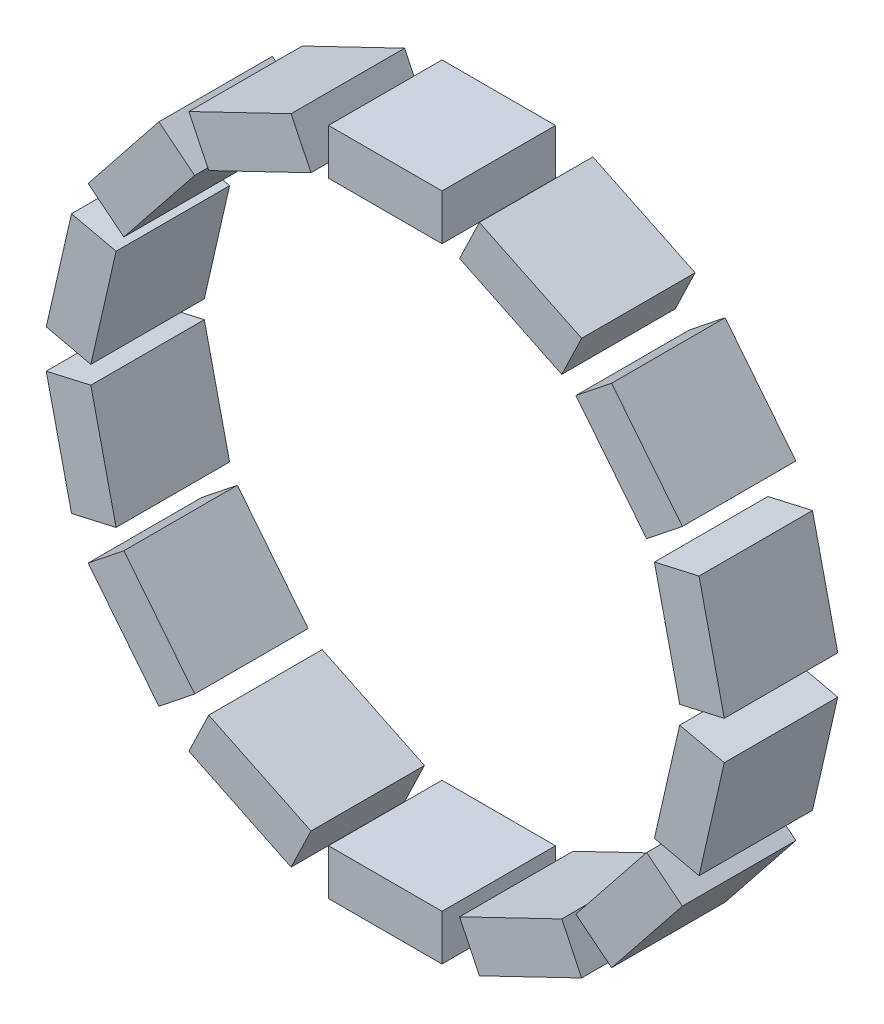
SolidWorks part; units mm, degrees
ref_plane "Front Plane" through (0, 0, 0) normal (0, 0, 1) x (1, 0, 0)
ref_plane "Top Plane" through (0, 0, 0) normal (0, 1, 0) x (1, 0, 0)
ref_plane "Right Plane" through (0, 0, 0) normal (1, 0, 0) x (0, 0, -1)
sketch "Sketch1" plane through (0, 0, 0) normal (0, 0, 1) x (1, 0, 0)
  line L0 (3.2594, 12.5053) -> (7.7448, 10.3452)
  line L1 (-2.4892, 14.6877) -> (2.4892, 14.6877)
  line L2 (-2.4892, 14.6877) -> (-2.4892, 12.6811)
  line L3 (-2.4892, 12.6811) -> (2.4892, 12.6811)
  line L4 (2.4892, 14.6877) -> (2.4892, 12.6811)
  line L5 (4.13, 14.3132) -> (3.2594, 12.5053)
  line L6 (4.13, 14.3132) -> (8.6154, 12.1531)
  line L7 (8.6154, 12.1531) -> (7.7448, 10.3452)
  line L8 (8.3625, 9.8526) -> (11.4664, 5.9604)
  line L9 (9.9313, 11.1037) -> (8.3625, 9.8526)
  line L10 (9.9313, 11.1037) -> (13.0353, 7.2115)
  line L11 (13.0353, 7.2115) -> (11.4664, 5.9604)
  line L12 (11.8092, 5.2486) -> (12.917, 0.395)
  line L13 (13.7655, 5.6951) -> (11.8092, 5.2486)
  line L14 (13.7655, 5.6951) -> (14.8733, 0.8415)
  line L15 (14.8733, 0.8415) -> (12.917, 0.395)
  line L16 (12.917, -0.395) -> (11.8092, -5.2486)
  line L17 (14.8733, -0.8415) -> (12.917, -0.395)
  line L18 (14.8733, -0.8415) -> (13.7655, -5.6951)
  line L19 (13.7655, -5.6951) -> (11.8092, -5.2486)
  line L20 (11.4664, -5.9604) -> (8.3625, -9.8526)
  line L21 (13.0353, -7.2115) -> (11.4664, -5.9604)
  line L22 (13.0353, -7.2115) -> (9.9313, -11.1037)
  line L23 (9.9313, -11.1037) -> (8.3625, -9.8526)
  line L24 (7.7448, -10.3452) -> (3.2594, -12.5053)
  line L25 (8.6154, -12.1531) -> (7.7448, -10.3452)
  line L26 (8.6154, -12.1531) -> (4.13, -14.3132)
  line L27 (4.13, -14.3132) -> (3.2594, -12.5053)
  line L28 (2.4892, -12.6811) -> (-2.4892, -12.6811)
  line L29 (2.4892, -14.6877) -> (2.4892, -12.6811)
  line L30 (2.4892, -14.6877) -> (-2.4892, -14.6877)
  line L31 (-2.4892, -14.6877) -> (-2.4892, -12.6811)
  line L32 (-3.2594, -12.5053) -> (-7.7448, -10.3452)
  line L33 (-4.13, -14.3132) -> (-3.2594, -12.5053)
  line L34 (-4.13, -14.3132) -> (-8.6154, -12.1531)
  line L35 (-8.6154, -12.1531) -> (-7.7448, -10.3452)
  line L36 (-8.3625, -9.8526) -> (-11.4664, -5.9604)
  line L37 (-9.9313, -11.1037) -> (-8.3625, -9.8526)
  line L38 (-9.9313, -11.1037) -> (-13.0353, -7.2115)
  line L39 (-13.0353, -7.2115) -> (-11.4664, -5.9604)
  line L40 (-11.8092, -5.2486) -> (-12.917, -0.395)
  line L41 (-13.7655, -5.6951) -> (-11.8092, -5.2486)
  line L42 (-13.7655, -5.6951) -> (-14.8733, -0.8415)
  line L43 (-14.8733, -0.8415) -> (-12.917, -0.395)
  line L44 (-12.917, 0.395) -> (-11.8092, 5.2486)
  line L45 (-14.8733, 0.8415) -> (-12.917, 0.395)
  line L46 (-14.8733, 0.8415) -> (-13.7655, 5.6951)
  line L47 (-13.7655, 5.6951) -> (-11.8092, 5.2486)
  line L48 (-11.4664, 5.9604) -> (-8.3625, 9.8526)
  line L49 (-13.0353, 7.2115) -> (-11.4664, 5.9604)
  line L50 (-13.0353, 7.2115) -> (-9.9313, 11.1037)
  line L51 (-9.9313, 11.1037) -> (-8.3625, 9.8526)
  line L52 (-7.7448, 10.3452) -> (-3.2594, 12.5053)
  line L53 (-8.6154, 12.1531) -> (-7.7448, 10.3452)
  line L54 (-8.6154, 12.1531) -> (-4.13, 14.3132)
  line L55 (-4.13, 14.3132) -> (-3.2594, 12.5053)
  dimension "D1" = 2.0066
  dimension "D2" = 4.9784
extrude "Extrude3" add sketch "Sketch1" along normal blind 4.9784
